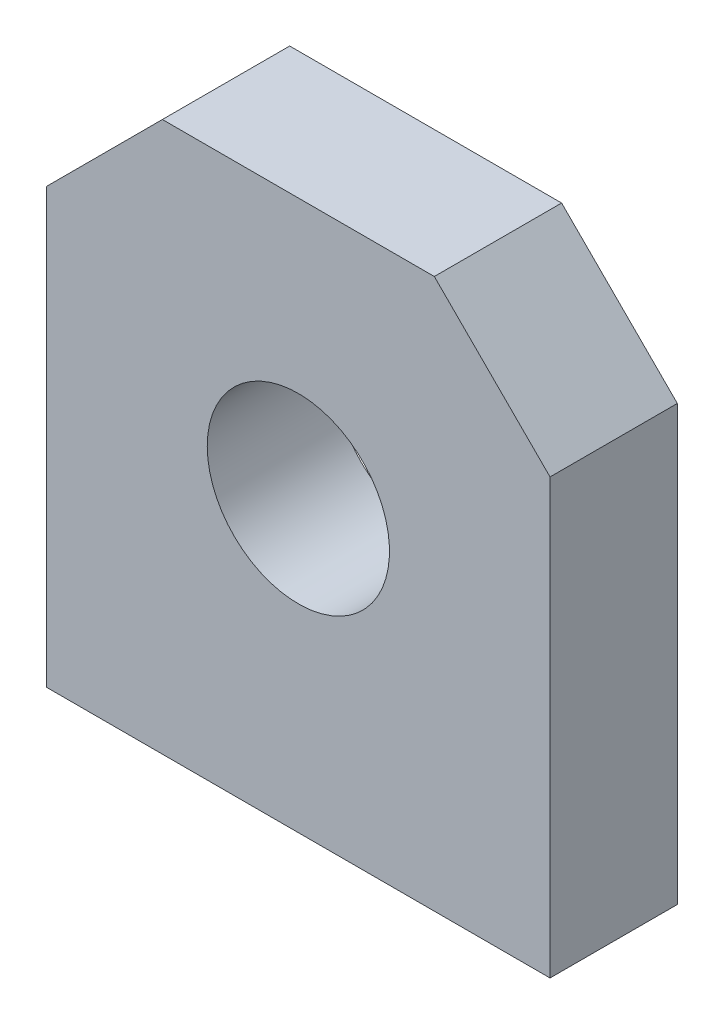
SolidWorks part; units mm, degrees
material "ABS PC"
ref_plane "Front Plane" through (0, 0, 0) normal (0, 0, 1) x (1, 0, 0)
ref_plane "Top Plane" through (0, 0, 0) normal (0, 1, 0) x (1, 0, 0)
ref_plane "Right Plane" through (0, 0, 0) normal (1, 0, 0) x (0, 0, -1)
sketch "Sketch1" plane through (0, 0, 0) normal (0, 0, 1) x (1, 0, 0)
  line L0 (-5.5245, 3.4925) -> (-2.9845, 6.0325)
  line L1 (-5.5245, -6.0325) -> (5.5245, -6.0325)
  line L2 (-5.5245, -6.0325) -> (-5.5245, 3.4925)
  line L3 (-2.9845, 6.0325) -> (2.9845, 6.0325)
  line L4 (5.5245, -6.0325) -> (5.5245, 3.4925)
  line L5 (-5.5245, -6.0325) -> (5.5245, 6.0325) construction
  line L6 (-5.5245, 6.0325) -> (5.5245, -6.0325) construction
  line L7 (5.5245, 3.4925) -> (2.9845, 6.0325)
  point P0 (0, 0)
  dimension "D1" = 11.049
  dimension "D2" = 12.065
extrude "Base" add sketch "Sketch1" along normal blind 2.794
sketch "Sketch2" plane through (0, 0, 0) normal (0, 0, -1) x (-1, 0, 0)
  line L0 (5.5245, -6.0325) -> (-5.5245, -6.0325) construction
  circle A0 centre (0, 0.3175) radius 2
  dimension "D2" = 4
  dimension "D1" = 6.35
extrude "BaseHole" cut sketch "Sketch2" against normal blind 2.794
